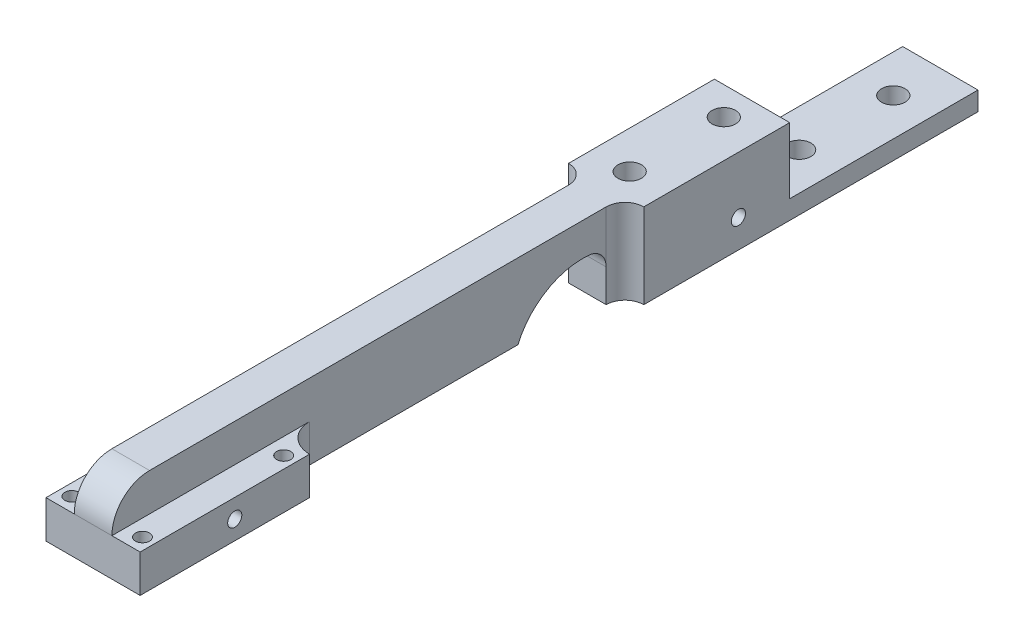
SolidWorks part; units mm, degrees
material "1060 Alloy"
ref_plane "Front Plane" through (0, 0, 0) normal (0, 0, 1) x (1, 0, 0)
ref_plane "Top Plane" through (0, 0, 0) normal (0, 1, 0) x (1, 0, 0)
ref_plane "Right Plane" through (0, 0, 0) normal (1, 0, 0) x (0, 0, -1)
sketch "Sketch1" plane through (0, 0, 0) normal (0, 0, 1) x (1, 0, 0)
  line L1 (10, -2) -> (-10, -2)
  line L2 (10, -2) -> (10, 6)
  line L3 (10, 6) -> (-10, 6)
  line L4 (-10, -2) -> (-10, 6)
  dimension "D1" = 8
  dimension "D2" = 20
  dimension "D3" = 2
  dimension "D4" = 10
extrude "Boss-Extrude1" add sketch "Sketch1" along normal blind 140
sketch "Sketch2" plane through (0, 6, 0) normal (0, 1, 0) x (1, 0, 0)
  line L0 (-10, -140) -> (-10, 0) construction
  line L1 (-10, 0) -> (-4, 0)
  line L2 (-10, 0) -> (-10, -104)
  line L3 (10, -104) -> (10, 0)
  line L4 (-4, 0) -> (-4, -98)
  line L6 (0, 0) -> (0, -135.4663) construction
  line L7 (10, 0) -> (-10, 0) construction
  line L9 (4, 0) -> (4, -98)
  line L12 (10, 0) -> (4, 0)
  arc A0 (-4, -98) -> (-10, -104) centre (-10, -98) cw
  arc A1 (4, -98) -> (10, -104) centre (10, -98) ccw
  dimension "D2" = 36
  dimension "D3" = 6
  dimension "D1" = 6
extrude "Cut-Extrude1" cut sketch "Sketch2" against normal through all
sketch "Sketch3" plane through (0, 0, 0) normal (1, 0, 0) x (0, 0, -1)
  line L0 (0, -2) -> (0, 6) construction
  line L1 (-140, 6) -> (0, 6)
  line L3 (-132, 14) -> (0, 14)
  line L4 (0, 6) -> (0, 14)
  arc A0 (-140, 6) -> (-132, 14) centre (-132, 6) cw
  dimension "D2" = 8
  dimension "D1" = 8
extrude "Boss-Extrude2" add sketch "Sketch3" along normal mid plane 8
sketch "Sketch4" plane through (4, 0, 0) normal (1, 0, 0) x (0, 0, -1)
  line L0 (0, -2) -> (-98, -2) construction
  line L1 (-140, -2) -> (-140, 6) construction
  line L2 (-35, -2) -> (-35, 2.9545)
  line L3 (-53.7477, -2) -> (-35, -2)
  arc A0 (-38.6364, 6.9379) -> (-53.7477, -2) centre (-40, -8) ccw
  arc A1 (-35, 2.9545) -> (-38.6364, 6.9379) centre (-39, 2.9545) ccw
  point P0 (-40, -8)
  point P3 (-140, 2)
  dimension "D3" = 30
  dimension "D5" = 8
  dimension "D1" = 6
  dimension "D2" = 100
  dimension "D4" = 5
extrude "Cut-Extrude2" cut sketch "Sketch4" against normal through all
sketch "Sketch6" plane through (0, 14, 0) normal (0, 1, 0) x (1, 0, 0)
  line L0 (0, 0) -> (0, -36.4214) construction
  line L1 (-4, 0) -> (-8, 0)
  line L2 (-4, -35) -> (4, -35)
  line L3 (8, 0) -> (8, -31)
  line L4 (-8, 0) -> (-8, -31)
  line L7 (4, 0) -> (8, 0)
  line L8 (-4, 0) -> (4, 0)
  arc A0 (-4, -35) -> (-8, -31) centre (-8, -35) ccw
  arc A1 (4, -35) -> (8, -31) centre (8, -35) cw
  dimension "D3" = 4
  dimension "D4" = 35
  dimension "D1" = 35
  dimension "D2" = 4
extrude "Boss-Extrude3" add sketch "Sketch6" against normal blind 18
sketch "Sketch7" plane through (0, 0, 0) normal (0, 0, -1) x (-1, 0, 0)
  line L0 (-8, -4) -> (-8, 14) construction
  line L1 (8, -4) -> (-8, -4)
  line L2 (8, -4) -> (8, 0)
  line L3 (8, 0) -> (-8, 0)
  line L4 (-8, -4) -> (-8, 0)
  dimension "D1" = 4
  dimension "D2" = 16
extrude "Boss-Extrude4" add sketch "Sketch7" along normal blind 40
sketch "Sketch8" plane through (0, 6, 0) normal (0, 1, 0) x (1, 0, 0)
  line L1 (10, -140) -> (4, -140) construction
  line L3 (0, 0) -> (0, -174.9903) construction
  line L4 (10, -140) -> (10, -104) construction
  circle A0 centre (7.5, -137) radius 1.5
  circle A1 centre (7.5, -107) radius 1.5
  circle A2 centre (-7.5, -107) radius 1.5
  circle A3 centre (-7.5, -137) radius 1.5
  dimension "D1" = 3
  dimension "D4" = 3
  dimension "D2" = 2.5
  dimension "D3" = 3
  dimension "D5" = 30
  dimension "D6" = 2.5
extrude "Cut-Extrude3" cut sketch "Sketch8" against normal through all
sketch "Sketch9" plane through (0, -2, 0) normal (0, -1, 0) x (1, 0, 0)
  line L1 (-7.5, 137) -> (7.5, 137)
  line L2 (-7.5, 137) -> (-7.5, 107)
  line L3 (-7.5, 107) -> (7.5, 107)
  line L4 (7.5, 137) -> (7.5, 107)
extrude "Cut-Extrude4" cut sketch "Sketch9" against normal blind 1.5
sketch "Sketch10" plane through (0, -2, 0) normal (0, -1, 0) x (1, 0, 0)
  line L0 (0, 0) -> (0, 146.0869) construction
  line L1 (-10, 140) -> (10, 140) construction
  line L2 (3, 79) -> (3, 65)
  line L3 (-3, 79) -> (-3, 65)
  arc A0 (-3, 65) -> (3, 65) centre (0, 65) ccw
  arc A1 (3, 79) -> (-3, 79) centre (0, 79) ccw
  dimension "D3" = 6
  dimension "D4" = 6
  dimension "D1" = 61
  dimension "D2" = 14
extrude "Cut-Extrude5" cut sketch "Sketch10" against normal blind 2
sketch "Sketch11" plane through (0, 14, 0) normal (0, 1, 0) x (1, 0, 0)
  line L0 (0, 0) -> (0, -150.3475) construction
  line L1 (-8, 0) -> (8, 0) construction
  line L2 (10, -140) -> (4, -140) construction
  circle A0 centre (0, -26) radius 2.5
  circle A1 centre (0, -6) radius 2.5
  dimension "D1" = 5
  dimension "D2" = 5
  dimension "D4" = 20
  dimension "D3" = 114
extrude "Cut-Extrude6" cut sketch "Sketch11" against normal through all
sketch "Sketch12" plane through (0, 0, 0) normal (0, 1, 0) x (1, 0, 0)
  line L0 (0, 0) -> (0, 46.0869) construction
  line L1 (-8, 40) -> (8, 40) construction
  circle A0 centre (0, 10) radius 2.5
  circle A1 centre (0, 30) radius 2.5
  dimension "D1" = 5
  dimension "D2" = 5
  dimension "D3" = 10
  dimension "D4" = 20
extrude "Cut-Extrude7" cut sketch "Sketch12" against normal through all
sketch "Sketch13" plane through (10, 0, 0) normal (1, 0, 0) x (0, 0, -1)
  line L0 (-140, -2) -> (-104, -2) construction
  line L1 (-140, -2) -> (-140, 6) construction
  circle A0 centre (-119.9, 2) radius 1.5
  dimension "D1" = 3
  dimension "D2" = 4
  dimension "D3" = 20.1
extrude "Cut-Extrude8" cut sketch "Sketch13" against normal blind 15
sketch "Sketch14" plane through (8, 0, 0) normal (1, 0, 0) x (0, 0, -1)
  line L0 (-140, -2) -> (-104, -2) construction
  line L1 (-140, -2) -> (-140, 6) construction
  circle A0 centre (-10.9, 2) radius 1.5
  dimension "D1" = 3
  dimension "D2" = 4
  dimension "D3" = 129.1
extrude "Cut-Extrude9" cut sketch "Sketch14" against normal blind 15
